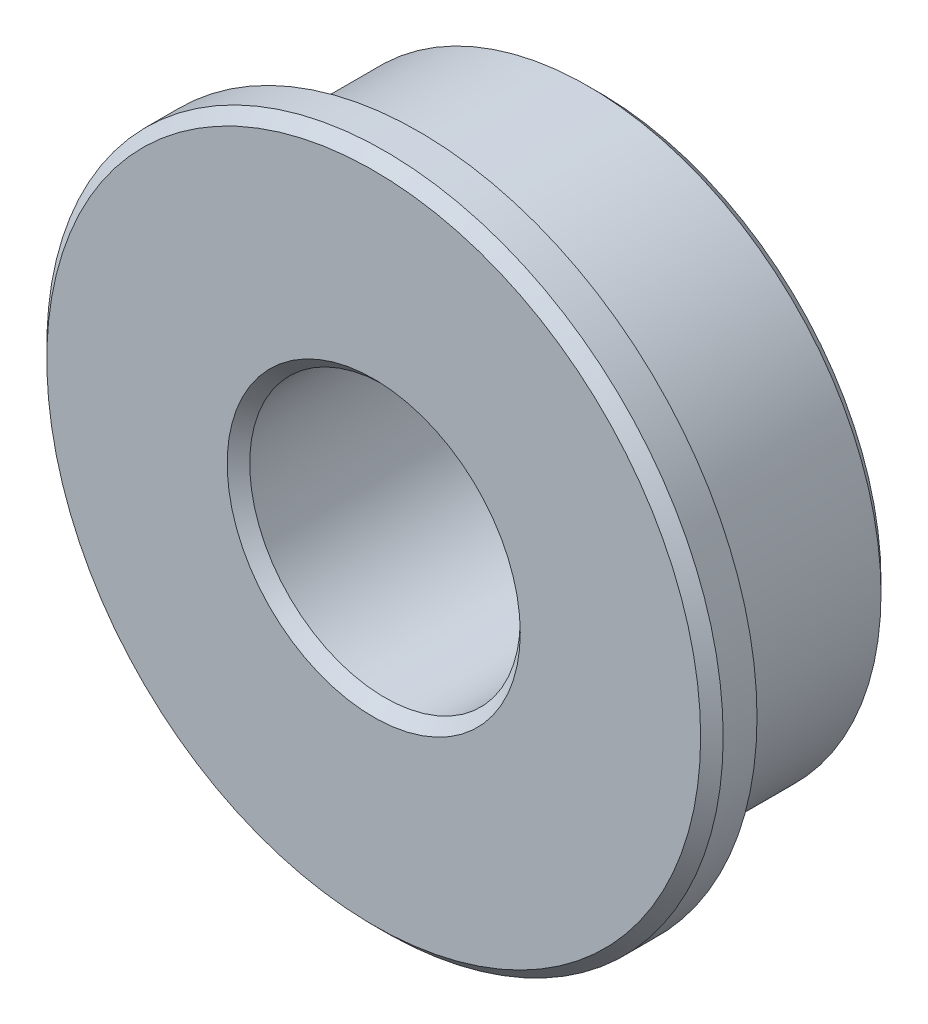
SolidWorks part; units mm, degrees
ref_plane "Front" through (0, 0, 0) normal (0, 0, 1) x (1, 0, 0)
ref_plane "Top" through (0, 0, 0) normal (0, 1, 0) x (1, 0, 0)
ref_plane "Right" through (0, 0, 0) normal (1, 0, 0) x (0, 0, -1)
sketch "Esquisse1" plane through (0, 0, 0) normal (0, 0, 1) x (1, 0, 0)
  circle A0 centre (0, 0) radius 3
  circle A1 centre (0, 0) radius 6.5
  dimension "D1" = 6
  dimension "D2" = 13
extrude "Boss.-Extru.1" add sketch "Esquisse1" along normal blind 5
sketch "Esquisse2" plane through (0, 0, 5) normal (0, 0, 1) x (1, 0, 0)
  circle A0 centre (0, 0) radius 7.5
  circle A1 centre (0, 0) radius 3
  dimension "D1" = 15
  dimension "D2" = 6
extrude "Boss.-Extru.2" add sketch "Esquisse2" against normal blind 1
chamfer "Chanfrein1" distance 0.25 angle 45 3 edges at (7.5, 0, 5) (3, 0, 5) (6.5, 0, 0)
